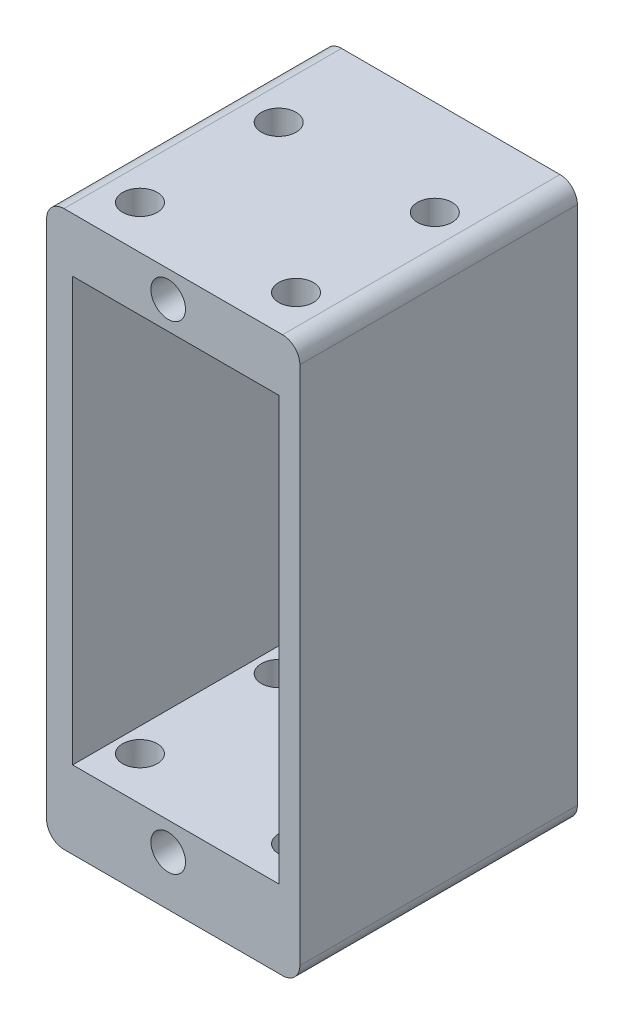
SolidWorks part; units mm, degrees
ref_plane "Front Plane" through (0, 0, 0) normal (0, 0, 1) x (1, 0, 0)
ref_plane "Top Plane" through (0, 0, 0) normal (0, 1, 0) x (1, 0, 0)
ref_plane "Right Plane" through (0, 0, 0) normal (1, 0, 0) x (0, 0, -1)
other "Graphic1"
sketch "Sketch2" plane through (0, 0, 0) normal (0, 0, 1) x (1, 0, 0)
  line L1 (-106.7177, 235.3278) -> (-92.1177, 235.3278)
  line L2 (-106.7177, 235.3278) -> (-106.7177, 203.3278)
  line L3 (-106.7177, 203.3278) -> (-92.1177, 203.3278)
  line L4 (-92.1177, 235.3278) -> (-92.1177, 203.3278)
  dimension "D1" = 14.6
  dimension "D2" = 32
extrude "Boss-Extrude1" add sketch "Sketch2" along normal blind 16
fillet "Fillet1" radius 1 4 edges at (-92.1177, 203.3278, 8) (-106.7177, 203.3278, 8) (-92.1177, 235.3278, 8) (-106.7177, 235.3278, 8)
sketch "Sketch3" plane through (0, 0, 16) normal (0, 0, 1) x (1, 0, 0)
  line L0 (-92.1177, 204.3278) -> (-92.1177, 234.3278) construction
  line L3 (-105.2177, 232.2) -> (-93.3177, 232.2)
  line L4 (-105.2177, 232.2) -> (-105.2177, 207.8)
  line L5 (-105.2177, 207.8) -> (-93.3177, 207.8)
  line L6 (-93.3177, 232.2) -> (-93.3177, 207.8)
  dimension "D1" = 11.9
  dimension "D2" = 24.4
  dimension "D3" = 1.2
extrude "Cut-Extrude1" cut sketch "Sketch3" against normal blind 16
sketch "Sketch4" plane through (0, 0, 16) normal (0, 0, 1) x (1, 0, 0)
  line L0 (-93.3177, 232.2) -> (-105.2177, 232.2) construction
  line L1 (-105.2177, 207.8) -> (-93.3177, 207.8) construction
  circle A0 centre (-99.7091, 233.8) radius 1
  circle A1 centre (-99.7091, 206.2) radius 1
  dimension "D1" = 1.6
  dimension "D2" = 1.6
extrude "Cut-Extrude2" cut sketch "Sketch4" against normal blind 16
sketch "Sketch5" plane through (0, 235.3278, 0) normal (0, 1, 0) x (1, 0, 0)
  line L0 (-123.5056, -5.5) -> (-84.1695, -5.5) construction
  line L1 (-103.8376, -5.5) -> (-103.8376, -13.5) construction
  circle A0 centre (-103.8376, -5.5) radius 1
  circle A1 centre (-94.8376, -5.5) radius 1
  circle A2 centre (-94.8376, -13.5) radius 1
  circle A3 centre (-103.8376, -13.5) radius 1
  dimension "D1" = 2
  dimension "D3" = 8
  dimension "D2" = 2
extrude "Cut-Extrude3" cut sketch "Sketch5" against normal through all
